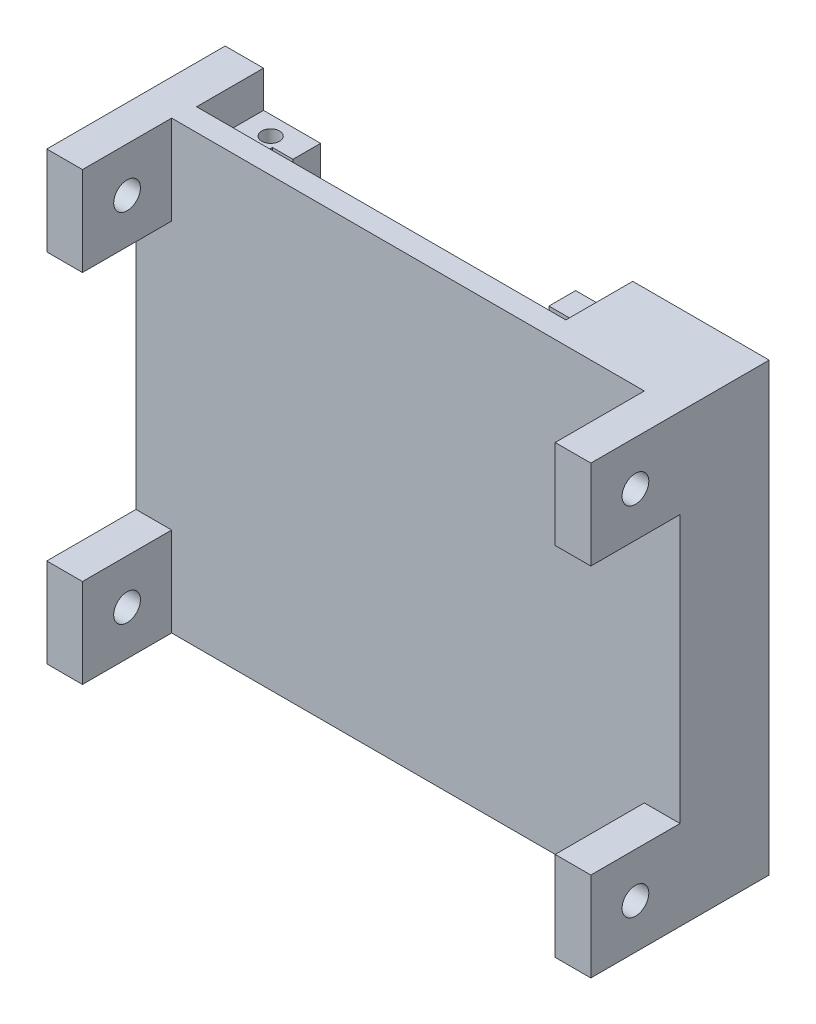
SolidWorks part; units mm, degrees
material "Polylactide (PLA)"
ref_plane "Front Plane" through (0, 0, 0) normal (0, 0, 1) x (1, 0, 0)
ref_plane "Top Plane" through (0, 0, 0) normal (0, 1, 0) x (1, 0, 0)
ref_plane "Right Plane" through (0, 0, 0) normal (1, 0, 0) x (0, 0, -1)
sketch "Sketch1" plane through (0, 0, 0) normal (0, 1, 0) x (1, 0, 0)
  line L0 (0, 0) -> (82.5, 0)
  line L1 (0, 0) -> (10, 0)
  line L2 (0, 0) -> (0, 20)
  line L3 (0, 20) -> (10, 20)
  line L4 (10, 0) -> (10, 20)
extrude "Boss-Extrude2" add sketch "Sketch1" along normal blind 10 contours L1 L4 L3 L2
sketch "Sketch3" plane through (0, 0, 0) normal (0, 1, 0) x (1, 0, 0)
  line L0 (0, 0) -> (82.5, 0)
  line L1 (0, 0) -> (10, 0) construction
  line L3 (82.5, 0) -> (72.5, 0)
  line L4 (82.5, 0) -> (82.5, 20)
  line L5 (82.5, 20) -> (72.5, 20)
  line L6 (72.5, 0) -> (72.5, 20)
extrude "Boss-Extrude3" add sketch "Sketch3" along normal blind 10 separate body contours L3 L6 L5 L4
sketch "Sketch4" plane through (0, 0, 0) normal (0, 1, 0) x (1, 0, 0)
  line L0 (10, 0) -> (10, 7.5)
  line L3 (10, 0) -> (10, 20) construction
  line L4 (72.5, 0) -> (72.5, 20) construction
  line L5 (10, 7.5) -> (72.5, 7.5)
  line L6 (10, 7.5) -> (10, 12.5)
  line L7 (10, 12.5) -> (72.5, 12.5)
  line L8 (72.5, 7.5) -> (72.5, 12.5)
extrude "Boss-Extrude4" add sketch "Sketch4" along normal blind 10 contours L5 L8 L7 L6
sketch "Sketch5" plane through (10, 0, 0) normal (1, 0, 0) x (0, 0, -1)
  line L0 (12.5, 0) -> (20, 10)
  line L1 (20, 0) -> (12.5, 10)
  line L2 (0, 10) -> (20, 10) construction
  circle A0 centre (16.25, 5) radius 0.5
sketch "Sketch6" plane through (10, 0, 0) normal (1, 0, 0) x (0, 0, -1)
  circle A0 centre (16.25, 5) radius 1
extrude "Cut-Extrude1" cut sketch "Sketch6" against normal blind 10
sketch "Sketch8" plane through (10, 0, 0) normal (1, 0, 0) x (0, 0, -1)
  line L0 (7.5, 0) -> (0, 10)
  line L1 (0, 10) -> (7.5, 10)
  line L2 (0, 10) -> (20, 10) construction
  line L3 (7.5, 10) -> (0, 0)
  circle A0 centre (3.75, 5) radius 1
sketch "Sketch10" plane through (72.5, 0, 0) normal (-1, 0, 0) x (0, 0, 1)
  circle A0 centre (-16.25, 5) radius 1
extrude "Cut-Extrude3" cut sketch "Sketch10" against normal blind 10 contours A0
sketch "Sketch11" plane through (0, 0, -12.5) normal (0, 0, -1) x (-1, 0, 0)
  line L0 (0, 10) -> (-35, 10)
  line L1 (-10, 10) -> (-72.5, 10) construction
  line L2 (-35, 10) -> (-35, 20)
  line L8 (-60, 45) -> (-10, 45)
  line L9 (-60, 45) -> (-60, -5)
  line L10 (-60, -5) -> (-10, -5)
  line L11 (-10, 45) -> (-10, -5)
  line L12 (-60, 45) -> (-10, -5) construction
  line L13 (-60, -5) -> (-10, 45) construction
sketch "Sketch16" plane through (10, 0, 0) normal (1, 0, 0) x (0, 0, -1)
  circle A0 centre (-1.6096, 5.0574) radius 1
sketch "Sketch17" plane through (72.5, 0, 0) normal (-1, 0, 0) x (0, 0, 1)
  circle A0 centre (-3.75, 5) radius 1
extrude "Boss-Extrude8" add sketch "Sketch11" against normal blind 10 contours L11 L10 L9 L8
sketch "Sketch18" plane through (0, 0, 0) normal (0, 0, 1) x (1, 0, 0)
  line L1 (0, 10) -> (10, 10)
  line L2 (0, 10) -> (0, 0)
  line L3 (0, 0) -> (10, 0)
  line L4 (10, 10) -> (10, 0)
extrude "Boss-Extrude9" add sketch "Sketch18" along normal blind 6
sketch "Sketch19" plane through (10, 0, 0) normal (1, 0, 0) x (0, 0, -1)
  circle A0 centre (-1.6096, 5.0574) radius 1
sketch "Sketch20" plane through (0, 0, 0) normal (0, -1, 0) x (1, 0, 0)
  line L0 (82.5, 0) -> (82.5, -20) construction
  line L1 (72.5, -12.5) -> (82.5, -12.5)
  line L2 (72.5, -12.5) -> (72.5, -2.5)
  line L3 (72.5, -2.5) -> (82.5, -2.5)
  line L4 (82.5, -12.5) -> (82.5, -2.5)
  line L5 (0, 6) -> (0, -20) construction
  line L6 (10, -2.5) -> (0, -2.5)
  line L7 (10, -2.5) -> (10, -12.5)
  line L8 (10, -12.5) -> (0, -12.5)
  line L9 (0, -2.5) -> (0, -12.5)
extrude "Boss-Extrude10" add sketch "Sketch20" along normal blind 12
sketch "Sketch21" plane through (72.5, 0, 0) normal (-1, 0, 0) x (0, 0, 1)
  circle A0 centre (-7.3635, -7.3831) radius 1
sketch "Sketch22" plane through (10, 0, 0) normal (1, 0, 0) x (0, 0, -1)
  circle A0 centre (7.5816, -8.9099) radius 1
sketch "Sketch23" plane through (0, 0, -12.5) normal (0, 0, -1) x (-1, 0, 0)
  line L0 (-60, 45) -> (-49.3, 45)
  line L3 (-60, 45) -> (-10, 45) construction
  line L5 (-49.3, 45) -> (-20.7, 45)
  line L6 (-49.3, 45) -> (-49.3, 0)
  line L7 (-49.3, 0) -> (-20.7, 0)
  line L8 (-20.7, 45) -> (-20.7, 0)
extrude "Cut-Extrude10" cut sketch "Sketch23" against normal blind 7.5 contours L6 L7 L8 L5
sketch "Sketch24" plane through (0, 45, 0) normal (0, 1, 0) x (1, 0, 0)
  line L1 (20.7, 12.5) -> (14.3, 12.5)
  line L2 (20.7, 12.5) -> (20.7, 5)
  line L3 (20.7, 5) -> (14.3, 5)
  line L4 (14.3, 12.5) -> (14.3, 5)
  line L5 (49.3, 12.5) -> (55.7, 12.5)
  line L6 (49.3, 12.5) -> (49.3, 5)
  line L7 (49.3, 5) -> (55.7, 5)
  line L8 (55.7, 12.5) -> (55.7, 5)
extrude "Cut-Extrude11" cut sketch "Sketch24" against normal blind 4.1
sketch "Sketch25" plane through (0, 40.9, 0) normal (0, 1, 0) x (1, 0, 0)
  line L1 (49.3, 5) -> (49.3, 7)
  line L2 (49.3, 5) -> (49.3, 12.5) construction
  line L4 (49.3, 7) -> (51.6, 7)
  line L5 (49.3, 7) -> (49.3, 9.5)
  line L6 (49.3, 9.5) -> (51.6, 9.5)
  line L7 (51.6, 7) -> (51.6, 9.5)
extrude "Cut-Extrude12" cut sketch "Sketch25" against normal blind 41 contours L4 L7 L6 L5
sketch "Sketch26" plane through (0, 40.9, 0) normal (0, 1, 0) x (1, 0, 0)
  line L0 (20.7, 5) -> (20.7, 7)
  line L1 (20.7, 5) -> (20.7, 12.5) construction
  line L3 (20.7, 7) -> (18.4, 7)
  line L4 (20.7, 7) -> (20.7, 9.4)
  line L5 (20.7, 9.4) -> (18.4, 9.4)
  line L6 (18.4, 7) -> (18.4, 9.4)
extrude "Cut-Extrude13" cut sketch "Sketch26" against normal blind 41 contours L3 L6 L5 L4
sketch "Sketch27" plane through (0, 40.9, 0) normal (0, 1, 0) x (1, 0, 0)
  line L1 (14.3, 12.5) -> (17.2, 12.5)
  line L2 (14.3, 12.5) -> (14.3, 10.4)
  line L3 (14.3, 10.4) -> (17.2, 10.4)
  line L4 (17.2, 12.5) -> (17.2, 10.4)
  circle A0 centre (17.2, 10.4) radius 1
extrude "Cut-Extrude14" cut sketch "Sketch27" against normal blind 10 contours A0
sketch "Sketch28" plane through (0, 40.9, 0) normal (0, 1, 0) x (1, 0, 0)
  line L1 (55.7, 12.5) -> (52.8, 12.5)
  line L2 (55.7, 12.5) -> (55.7, 10.4)
  line L3 (55.7, 10.4) -> (52.8, 10.4)
  line L4 (52.8, 12.5) -> (52.8, 10.4)
  circle A0 centre (52.8, 10.4) radius 1
extrude "Cut-Extrude15" cut sketch "Sketch28" against normal blind 10 contours A0
sketch "Sketch30" plane through (0, 40.9, 0) normal (0, 1, 0) x (1, 0, 0)
  line L0 (17.2, 10.4) -> (52.8, 10.4)
sketch "Sketch31" plane through (0, 0, -7.5) normal (0, 0, 1) x (1, 0, 0)
  line L4 (72.5, 10) -> (60, 10)
  line L5 (60, 10) -> (60, 0)
  line L6 (60, 0) -> (72.5, 0)
  line L7 (72.5, 0) -> (72.5, 10)
  line L8 (72.5, 10) -> (60, 10)
  line L9 (60, 10) -> (60, 0)
  line L10 (60, 0) -> (72.5, 0)
  line L11 (72.5, 0) -> (72.5, 10)
  dimension "D1" = 0
extrude "Boss-Extrude11" add sketch "Sketch31" along normal blind 5 contours L11 L8 L9 L10
sketch "Sketch32" plane through (0, 0, -20) normal (0, 0, -1) x (-1, 0, 0)
  line L4 (-82.5, 0) -> (-72.5, 0)
  line L5 (-72.5, 0) -> (-72.5, 10)
  line L6 (-72.5, 10) -> (-82.5, 10)
  line L7 (-82.5, 10) -> (-82.5, 0)
  line L8 (-82.5, 0) -> (-72.5, 0)
  line L9 (-72.5, 0) -> (-72.5, 10)
  line L10 (-72.5, 10) -> (-82.5, 10)
  line L11 (-82.5, 10) -> (-82.5, 0)
  dimension "D1" = 0
extrude "Cut-Extrude16" cut sketch "Sketch32" against normal blind 7.5
sketch3d "3DSketch1"
  line L4 (10, 0, -20) -> (0, 0, -20)
  line L5 (0, 0, -20) -> (0, 10, -20)
  line L6 (0, 10, -20) -> (10, 10, -20)
  line L7 (10, 10, -20) -> (10, 0, -20)
  line L8 (10, 0, -20) -> (0, 0, -20)
  line L9 (0, 0, -20) -> (0, 10, -20)
  line L10 (0, 10, -20) -> (10, 10, -20)
  line L11 (10, 10, -20) -> (10, 0, -20)
  dimension "D1" = 0
extrude "Cut-Extrude17" cut sketch "3DSketch1" along direction (0, 0, -1) on the side of the normal blind 7.5
sketch "Sketch33" plane through (0, -12, 0) normal (0, -1, 0) x (1, 0, 0)
  line L4 (10, -12.5) -> (10, -2.5)
  line L5 (10, -2.5) -> (0, -2.5)
  line L6 (0, -2.5) -> (0, -12.5)
  line L7 (0, -12.5) -> (10, -12.5)
  line L8 (10, -12.5) -> (10, -2.5)
  line L9 (10, -2.5) -> (0, -2.5)
  line L10 (0, -2.5) -> (0, -12.5)
  line L11 (0, -12.5) -> (10, -12.5)
  dimension "D1" = 0
extrude "Boss-Extrude12" add sketch "Sketch33" along normal blind 5
sketch "Sketch34" plane through (0, -12, 0) normal (0, -1, 0) x (1, 0, 0)
  line L4 (72.5, -2.5) -> (72.5, -12.5)
  line L5 (72.5, -12.5) -> (82.5, -12.5)
  line L6 (82.5, -12.5) -> (82.5, -2.5)
  line L7 (82.5, -2.5) -> (72.5, -2.5)
  line L8 (72.5, -2.5) -> (72.5, -12.5)
  line L9 (72.5, -12.5) -> (82.5, -12.5)
  line L10 (82.5, -12.5) -> (82.5, -2.5)
  line L11 (82.5, -2.5) -> (72.5, -2.5)
  dimension "D1" = 0
extrude "Boss-Extrude13" add sketch "Sketch34" along normal blind 5
sketch "Sketch35" plane through (0, 0, 6) normal (0, 0, 1) x (1, 0, 0)
  line L4 (0, 10) -> (0, 0)
  line L5 (0, 0) -> (10, 0)
  line L6 (10, 0) -> (10, 10)
  line L7 (10, 10) -> (0, 10)
  line L8 (0, 10) -> (0, 0)
  line L9 (0, 0) -> (10, 0)
  line L10 (10, 0) -> (10, 10)
  line L11 (10, 10) -> (0, 10)
  dimension "D1" = 0
extrude "Boss-Extrude14" add sketch "Sketch35" along normal blind 3.5
sketch "Sketch36" plane through (0, 0, 0) normal (0, 0, 1) x (1, 0, 0)
  line L4 (72.5, 0) -> (82.5, 0)
  line L5 (82.5, 0) -> (82.5, 10)
  line L6 (82.5, 10) -> (72.5, 10)
  line L7 (72.5, 10) -> (72.5, 0)
  line L8 (72.5, 0) -> (82.5, 0)
  line L9 (82.5, 0) -> (82.5, 10)
  line L10 (82.5, 10) -> (72.5, 10)
  line L11 (72.5, 10) -> (72.5, 0)
  dimension "D1" = 0
extrude "Boss-Extrude15" add sketch "Sketch36" along normal blind 9.5
sketch "Sketch37" plane through (10, 0, 0) normal (1, 0, 0) x (0, 0, -1)
  line L0 (-9.5, 10) -> (2.5, 0)
  line L1 (2.5, 0) -> (-9.5, 0)
  line L2 (-9.5, 0) -> (2.5, 10)
  circle A0 centre (-3.5, 5) radius 1.25
sketch "Sketch38" plane through (10, 0, 0) normal (1, 0, 0) x (0, 0, -1)
  line L0 (2.5, -5) -> (12.5, -17)
  line L1 (12.5, -17) -> (12.5, -5)
  line L2 (12.5, -5) -> (2.5, -17)
  circle A0 centre (7.5, -11) radius 1.25
extrude "Cut-Extrude18" cut sketch "Sketch37" against normal blind 15.5 and the other way blind 90.5 contours A0
extrude "Cut-Extrude19" cut sketch "Sketch38" against normal blind 15.5 and the other way blind 88.5 contours A0
sketch "Sketch39" plane through (0, 0, -12.5) normal (0, 0, -1) x (-1, 0, 0)
  line L0 (-60, 45) -> (-60, 10) construction
  line L1 (-60, 11.6104) -> (-89.9671, 11.6104)
  line L2 (-60, 11.6104) -> (-60, -20.2254)
  line L3 (-60, -20.2254) -> (-89.9671, -20.2254)
  line L4 (-89.9671, 11.6104) -> (-89.9671, -20.2254)
  line L5 (-10, 45) -> (-10, 10) construction
  line L6 (-10, 12.6125) -> (5.6172, 12.6125)
  line L7 (-10, 12.6125) -> (-10, -19.6858)
  line L8 (-10, -19.6858) -> (5.6172, -19.6858)
  line L9 (5.6172, 12.6125) -> (5.6172, -19.6858)
extrude "Cut-Extrude20" cut sketch "Sketch39" against normal blind 36
sketch "Sketch40" plane through (60, 0, 0) normal (1, 0, 0) x (0, 0, -1)
  line L4 (2.5, 45) -> (2.5, -5)
  line L5 (2.5, -5) -> (12.5, -5)
  line L6 (12.5, -5) -> (12.5, 45)
  line L7 (12.5, 45) -> (2.5, 45)
  line L8 (2.5, 45) -> (2.5, -5)
  line L9 (2.5, -5) -> (12.5, -5)
  line L10 (12.5, -5) -> (12.5, 45)
  line L11 (12.5, 45) -> (2.5, 45)
  dimension "D1" = 0
extrude "Boss-Extrude16" add sketch "Sketch40" along normal blind 11
sketch "Sketch41" plane through (0, 0, -2.5) normal (0, 0, 1) x (1, 0, 0)
  line L1 (10, 45) -> (14, 45)
  line L2 (10, 45) -> (10, 35)
  line L3 (10, 35) -> (14, 35)
  line L4 (14, 45) -> (14, 35)
  line L5 (10, -5) -> (14, -5)
  line L6 (10, -5) -> (10, 5)
  line L7 (10, 5) -> (14, 5)
  line L8 (14, -5) -> (14, 5)
  line L9 (71, 45) -> (67, 45)
  line L10 (71, 45) -> (71, 35)
  line L11 (71, 35) -> (67, 35)
  line L12 (67, 45) -> (67, 35)
  line L13 (71, -5) -> (67, -5)
  line L14 (71, -5) -> (71, 5)
  line L15 (71, 5) -> (67, 5)
  line L16 (67, -5) -> (67, 5)
extrude "Boss-Extrude17" add sketch "Sketch41" along normal blind 10
sketch "Sketch42" plane through (71, 0, 0) normal (1, 0, 0) x (0, 0, -1)
  line L0 (-7.5, -5) -> (12.5, -5) construction
  line L1 (-7.5, -5) -> (-7.5, 5) construction
  line L2 (-7.5, 35) -> (2.5, 35) construction
  line L3 (-7.5, 35) -> (-7.5, 45) construction
  circle A0 centre (-2.5, 0) radius 1.5
  circle A1 centre (-2.5, 40) radius 1.5
  dimension "D1" = 5
  dimension "D3" = 5
  dimension "D2" = 5
  dimension "D4" = 5
extrude "Cut-Extrude21" cut sketch "Sketch42" against normal blind 80
